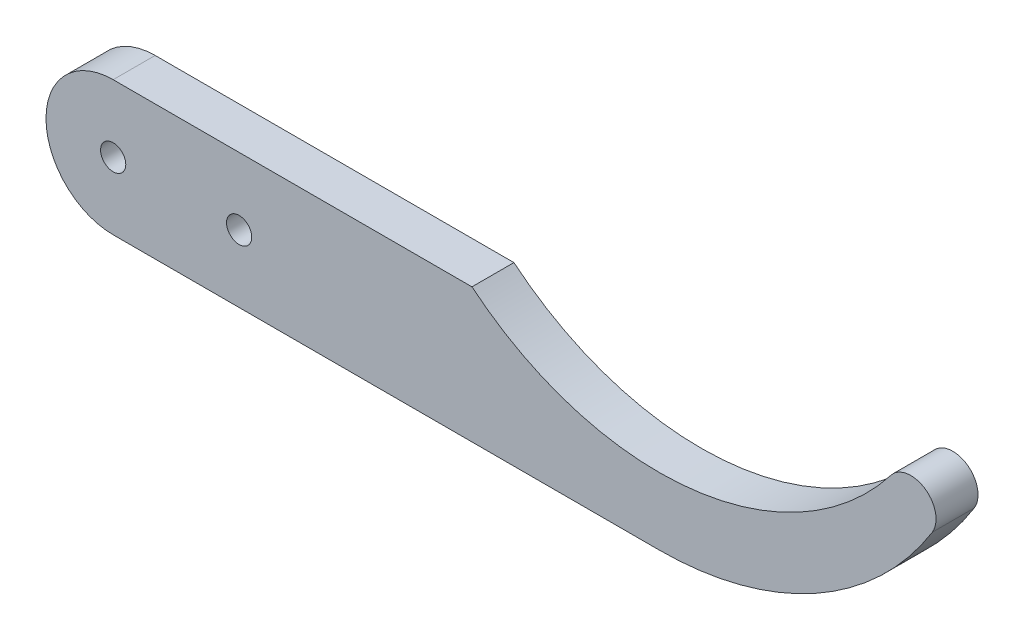
SolidWorks part; units mm, degrees
ref_plane "Plan de face" through (0, 0, 0) normal (0, 0, 1) x (1, 0, 0)
ref_plane "Plan de dessus" through (0, 0, 0) normal (0, 1, 0) x (1, 0, 0)
ref_plane "Plan de droite" through (0, 0, 0) normal (1, 0, 0) x (0, 0, -1)
sketch "Esquisse1" plane through (0, 0, 0) normal (0, 0, 1) x (1, 0, 0)
  line L0 (0, 0) -> (80, 0) construction
  line L1 (20, 0) -> (20, 23.8674) construction
  line L2 (0, 0) -> (0, 35) construction
  line L3 (0, 35) -> (50, 35) construction
  line L4 (0, 8) -> (20, 8)
  line L5 (77.6316, 13.5175) -> (80, 11.6762) construction
  line L6 (20, 8) -> (27.7289, 8)
  line L7 (0, -8) -> (50, -8)
  line L8 (50, 35) -> (50, -8) construction
  line L9 (0, 8) -> (-15, 8)
  line L10 (0, 0) -> (-15, 0) construction
  line L11 (0, -8) -> (-15, -8)
  circle A0 centre (0, 0) radius 1.5
  arc A1 (0, 8) -> (0, -8) centre (0, 0) ccw construction
  circle A2 centre (50, 35) radius 35 construction
  arc A3 (27.7289, 8) -> (77.6316, 13.5175) centre (50, 35) ccw
  arc A4 (77.6316, 13.5175) -> (82.5479, 10.0925) centre (80, 11.6762) cw
  arc A5 (50, -8) -> (82.5479, 10.0925) centre (50, 30.3227) ccw
  circle A6 centre (15, 0) radius 1.5 construction
  arc A7 (-15, 8) -> (-15, -8) centre (-15, 0) ccw
  circle A8 centre (-15, 0) radius 1.5
  dimension "D3" = 3
  dimension "D4" = 35
  dimension "D6" = 70
  dimension "D7" = 3
  dimension "D8" = 8
  dimension "D9" = 30
  dimension "D10" = 15
  dimension "D11" = 8
  dimension "D1" = 20
  dimension "D2" = 80
  dimension "D5" = 50
  dimension "D12" = 15
extrude "Boss.-Extru.1" add sketch "Esquisse1" along normal blind 5
